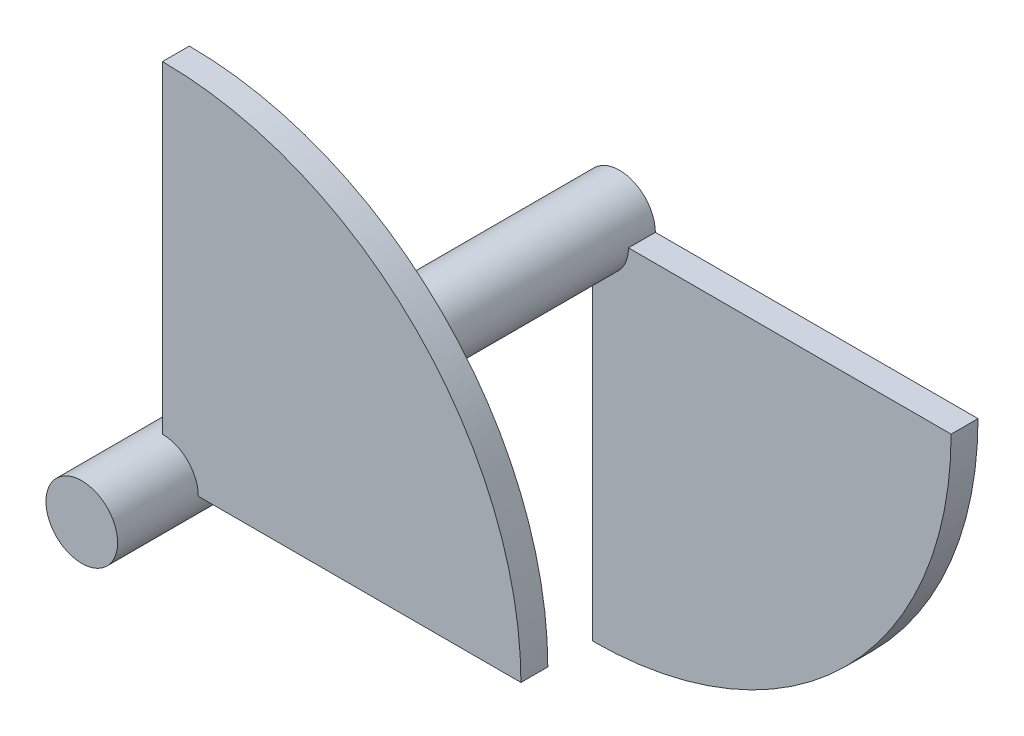
SolidWorks part; units mm, degrees
ref_plane "前视基准面" through (0, 0, 0) normal (0, 0, 1) x (1, 0, 0)
ref_plane "上视基准面" through (0, 0, 0) normal (0, 1, 0) x (1, 0, 0)
ref_plane "右视基准面" through (0, 0, 0) normal (1, 0, 0) x (0, 0, -1)
sketch "草图1" plane through (0, 0, 0) normal (0, 0, 1) x (1, 0, 0)
  circle A0 centre (0, 0) radius 4
  dimension "D1" = 8
extrude "凸台-拉伸1" add sketch "草图1" along normal blind 60
sketch "草图2" plane through (0, 0, 0) normal (0, 1, 0) x (1, 0, 0)
  line L0 (0, 2.7613) -> (0, -69.4172) construction
  line L1 (0, 0) -> (40, 0) construction
  line L2 (0, 0) -> (0, -3) construction
  line L3 (0, -3) -> (40, -3) construction
  line L4 (40, 0) -> (40, -3) construction
  line L6 (0, -48) -> (40, -48)
  line L7 (0, -48) -> (0, -51)
  line L8 (0, -51) -> (40, -51)
  line L9 (40, -48) -> (40, -51)
  dimension "D1" = 3
  dimension "D2" = 40
  dimension "D3" = 45
ref_axis "基准轴1" through (0, 0, -6.3703) along (0, 0, 1)
revolve "旋转1" add sketch "草图2" angle 90 about L0
sketch "草图3" plane through (0, 0, 0) normal (0, 1, 0) x (1, 0, 0)
  line L0 (40, -48) -> (0, -48) construction
  line L1 (0, 0) -> (40, 0)
  line L2 (0, 0) -> (0, -3)
  line L3 (0, -3) -> (40, -3)
  line L4 (40, 0) -> (40, -3)
  line L5 (40, -51) -> (40, -48) construction
revolve "旋转2" add sketch "草图3" angle 90 about axis through (0, 0, -6.3703) along (0, 0, 1)
